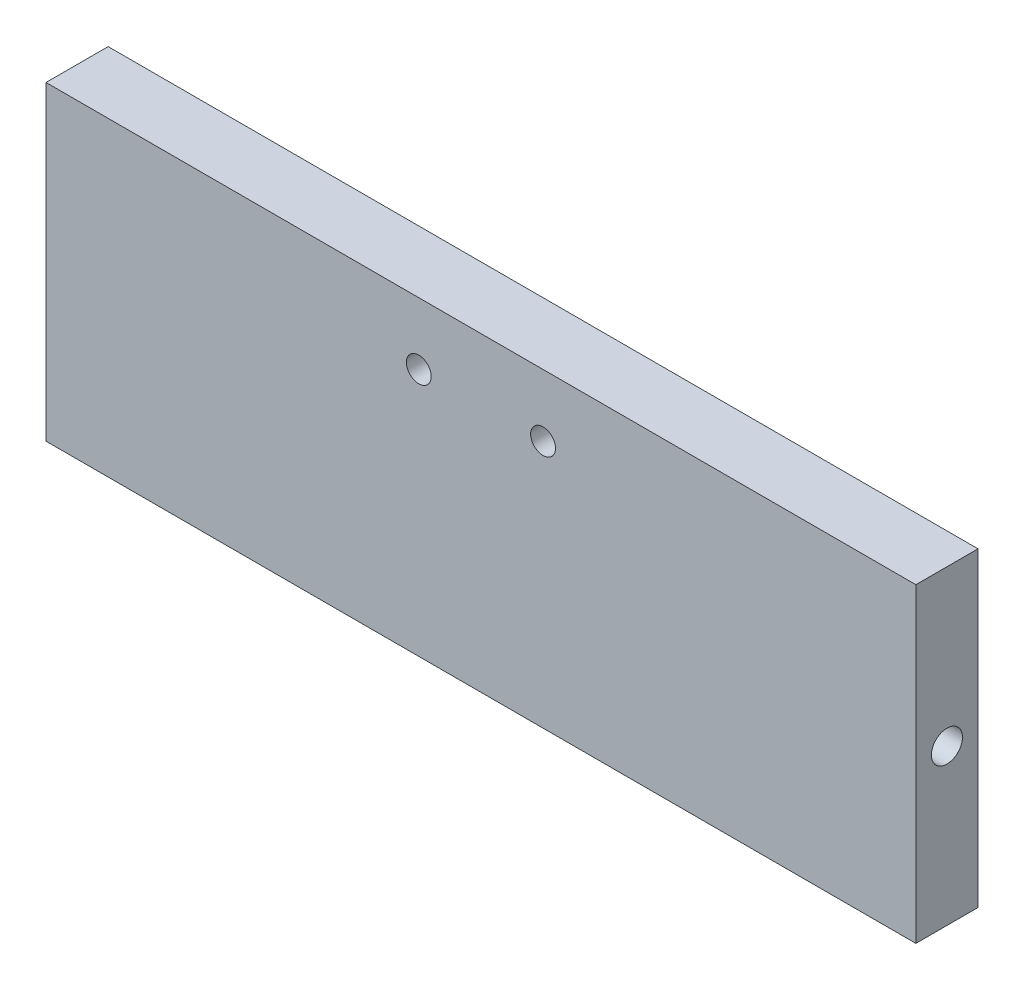
SolidWorks part; units mm, degrees
ref_plane "Front Plane" through (0, 0, 0) normal (0, 0, 1) x (1, 0, 0)
ref_plane "Top Plane" through (0, 0, 0) normal (0, 1, 0) x (1, 0, 0)
ref_plane "Right Plane" through (0, 0, 0) normal (1, 0, 0) x (0, 0, -1)
sketch "Sketch1" plane through (0, 0, 0) normal (0, 0, 1) x (1, 0, 0)
  line L0 (0, 0) -> (0, 15.7454) construction
  line L1 (-70, -25) -> (70, -25)
  line L2 (-70, -25) -> (-70, 25)
  line L3 (-70, 25) -> (70, 25)
  line L4 (70, -25) -> (70, 25)
  line L5 (-70, -25) -> (70, 25) construction
  line L6 (-70, 25) -> (70, -25) construction
  circle A0 centre (-10, 15) radius 2
  circle A1 centre (10, 15) radius 2
  point P0 (0, 0)
  dimension "D3" = 4
  dimension "D1" = 50
  dimension "D2" = 140
  dimension "D4" = 10
  dimension "D5" = 10
extrude "Boss-Extrude1" add sketch "Sketch1" along normal blind 10
sketch "Sketch2" plane through (70, 0, 0) normal (1, 0, 0) x (0, 0, -1)
  line L0 (-10, 25) -> (0, 25) construction
  circle A0 centre (-5, 0) radius 2.5
  point P2 (0, 0)
  point P4 (0, 0)
  point P7 (-5, 25)
  dimension "D1" = 5
extrude "Cut-Extrude1" cut sketch "Sketch2" against normal blind 153
